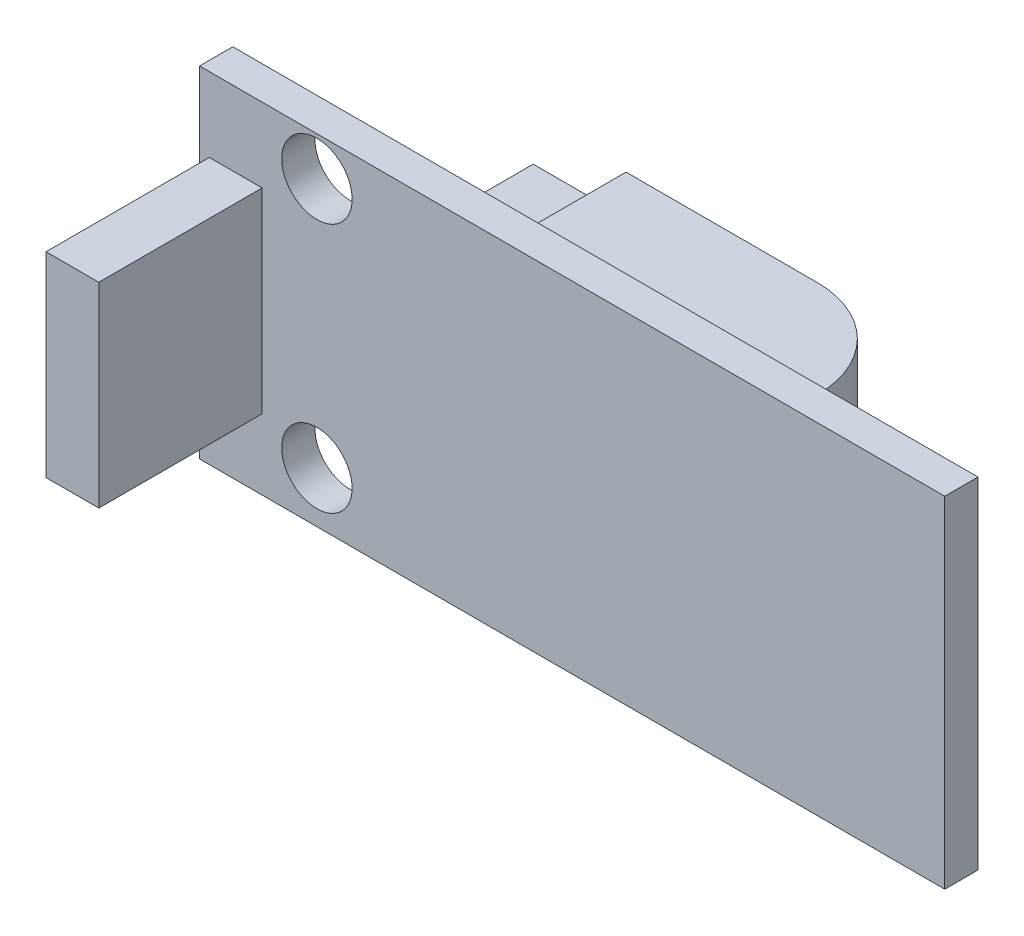
SolidWorks part; units mm, degrees
ref_plane "Alzado" through (0, 0, 0) normal (1, 0, 0) x (0, 1, 0)
ref_plane "Planta" through (0, 0, 0) normal (0, 0, 1) x (0, 1, 0)
ref_plane "Vista lateral" through (0, 0, 0) normal (0, 1, 0) x (-1, 0, 0)
sketch "Croquis1" plane through (0, 0, 0) normal (0, 0, 1) x (0, 1, 0)
  line L1 (-8.7, -19.05) -> (8.7, -19.05)
  line L2 (-8.7, -19.05) -> (-8.7, 19.05)
  line L3 (-8.7, 19.05) -> (8.7, 19.05)
  line L4 (8.7, -19.05) -> (8.7, 19.05)
  line L5 (-8.7, -19.05) -> (8.7, 19.05) construction
  line L6 (-8.7, 19.05) -> (8.7, -19.05) construction
  circle A0 centre (6.7, 13.05) radius 1.8
  circle A1 centre (-6.1, 13.05) radius 1.8
  point P0 (0, 0)
  point P10 (0, 0)
  point P11 (7.0225, 11.0664)
  point P12 (-7.0537, 11.0664)
  point P13 (-7.0088, 10.7516)
  point P14 (6.5727, 10.5717)
  dimension "D1" = 3.6
  dimension "D2" = 4.2
  dimension "D3" = 0.8
  dimension "D4" = 0.2
  dimension "D5" = 9.2
  dimension "D6" = 38.1
extrude "Saliente-Extruir1" add sketch "Croquis1" along normal blind 1.7
sketch "Croquis2" plane through (0, 0, 1.7) normal (0, 0, 1) x (1, 0, 0)
  line L0 (-19.05, 8.7) -> (-19.05, -8.7) construction
  line L1 (-18.55, 4.9) -> (-15.85, 4.9)
  line L2 (-18.55, 4.9) -> (-18.55, -5.1)
  line L3 (-18.55, -5.1) -> (-15.85, -5.1)
  line L4 (-15.85, 4.9) -> (-15.85, -5.1)
  circle A0 centre (-13.05, 6.7) radius 1.8 construction
  dimension "D1" = 10
  dimension "D2" = 2.7
  dimension "D3" = 0.5
extrude "Saliente-Extruir2" add sketch "Croquis2" along normal blind 8.35 and the other way blind 2.35
sketch "Croquis3" plane through (0, 0, 0) normal (0, 0, -1) x (1, 0, 0)
  line L1 (-10.6906, -4.1823) -> (-5.9445, -4.1823)
  line L2 (-10.6906, -4.1823) -> (-10.6906, 4.4642)
  line L3 (-10.6906, 4.4642) -> (-5.8505, 4.4642)
  line L4 (1.7152, -2.3966) -> (1.7152, 2.4906)
  line L5 (-5.9445, -6.2029) -> (8.811, -6.2029)
  line L6 (-5.9445, -6.2029) -> (-5.9445, -4.1823)
  line L7 (1.7152, -2.3966) -> (8.811, -2.3966)
  line L8 (8.811, -6.2029) -> (8.811, -2.3966)
  line L9 (1.7152, 2.4906) -> (8.811, 2.4906)
  line L10 (-5.8505, 4.4642) -> (-5.8505, 6.1089)
  line L11 (-5.8505, 6.1089) -> (8.811, 6.1089)
  line L12 (8.811, 2.4906) -> (8.811, 6.1089)
  point P12 (-5.8975, 2.4906)
  point P13 (-5.8505, 6.1089)
extrude "Saliente-Extruir3" add sketch "Croquis3" along normal blind 7
fillet "Redondeo2" radius 5 2 edges at (8.811, -4.2997, -7) (8.811, 4.2997, -7)
